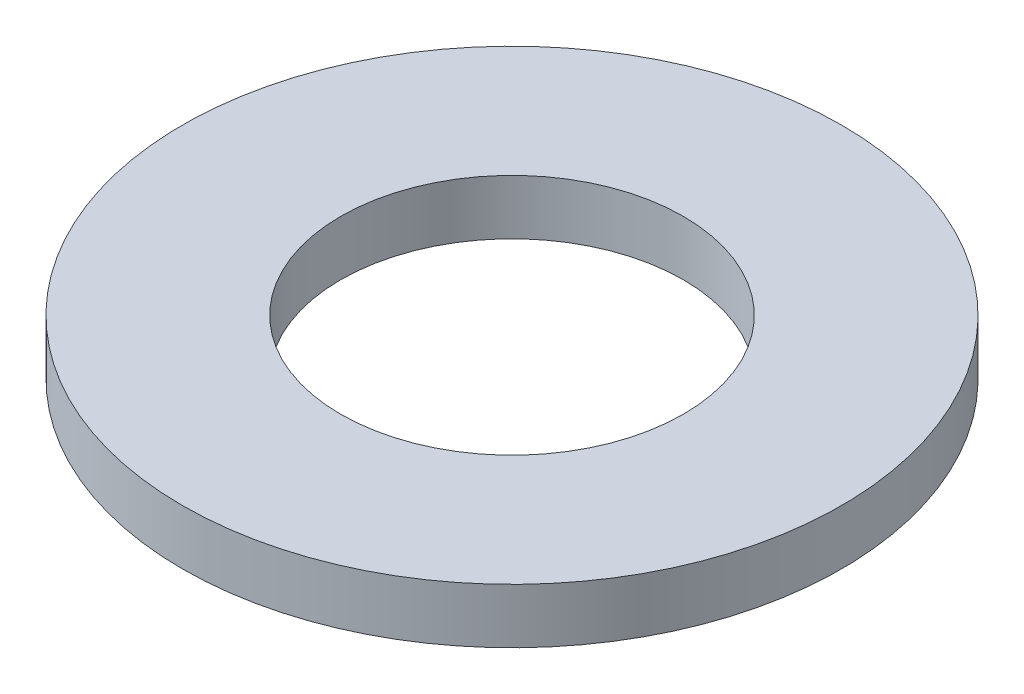
SolidWorks part; units mm, degrees
ref_plane "Front Plane" through (0, 0, 0) normal (0, 0, 1) x (1, 0, 0)
ref_plane "Top Plane" through (0, 0, 0) normal (0, 1, 0) x (1, 0, 0)
ref_plane "Right Plane" through (0, 0, 0) normal (1, 0, 0) x (0, 0, -1)
sketch "Sketch1" plane through (0, 0, 0) normal (0, 1, 0) x (1, 0, 0)
  circle A0 centre (0, 0) radius 39.624
  circle A1 centre (0, 0) radius 76.2
  dimension "D1" = 152.4
  dimension "D2" = 79.248
extrude "Boss-Extrude1" add sketch "Sketch1" along normal blind 12.7
